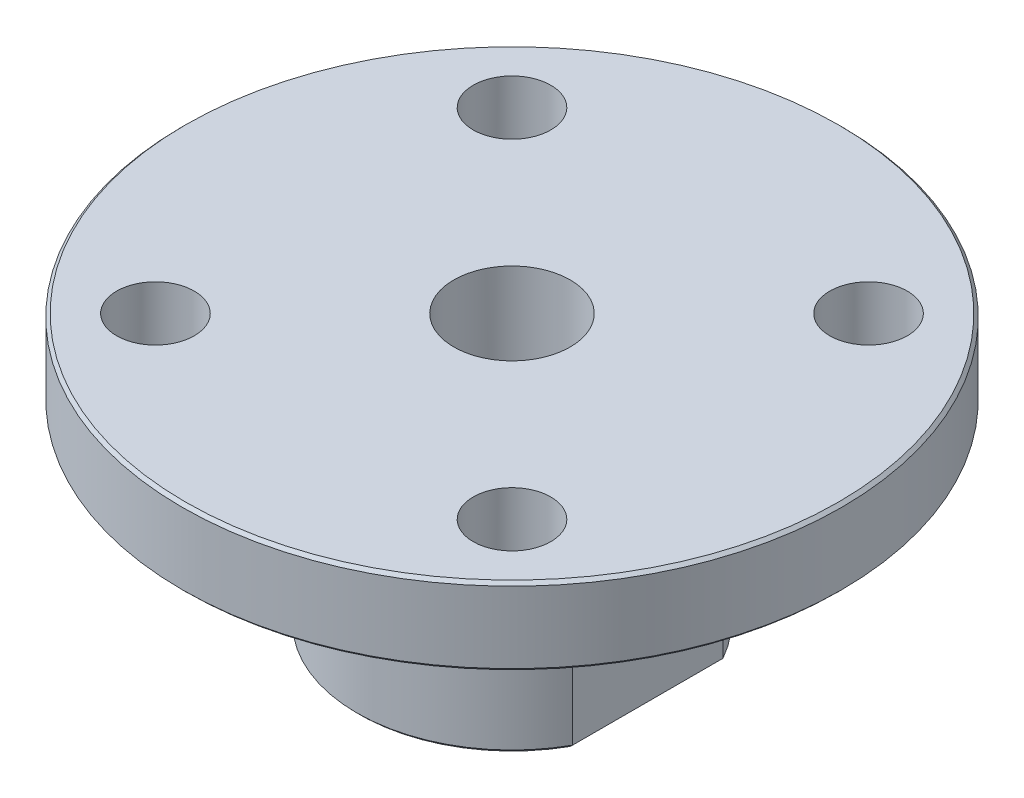
SolidWorks part; units mm, degrees
ref_plane "Front Plane" through (0, 0, 0) normal (0, 0, 1) x (1, 0, 0)
ref_plane "Top Plane" through (0, 0, 0) normal (0, 1, 0) x (1, 0, 0)
ref_plane "Right Plane" through (0, 0, 0) normal (1, 0, 0) x (0, 0, -1)
sketch "Sketch1" plane through (0, 0, 0) normal (0, 0, 1) x (1, 0, 0)
  line L0 (0, 0) -> (0, 50.6683) construction
  line L1 (6.35, 0) -> (6.35, 7.9375)
  line L2 (6.35, 7.9375) -> (13.4937, 7.9375)
  line L3 (13.4937, 7.9375) -> (13.4937, 11.1125)
  line L4 (13.4937, 11.1125) -> (2.3812, 11.1125)
  line L5 (6.35, 0) -> (2.3813, 0)
  line L6 (2.3813, 0) -> (2.3812, 11.1125)
  dimension "D1" = 7.9375
  dimension "D2" = 3.175
  dimension "D3" = 26.9875
  dimension "D4" = 4.7625
  dimension "D5" = 12.7
revolve "Revolve1" add sketch "Sketch1" angle 360 about L0
sketch "Sketch2" plane through (0, 0, 0) normal (0, -1, 0) x (1, 0, 0)
  line L0 (0, 0) -> (0, 11.4258) construction
  line L1 (7.1437, 3.0742) -> (5.5562, -3.0742) construction
  line L2 (-7.1437, -3.0742) -> (-5.5562, -3.0742)
  line L3 (-7.1437, -3.0742) -> (-7.1437, 3.0742)
  line L4 (-7.1437, 3.0742) -> (-5.5562, 3.0742)
  line L5 (-5.5562, -3.0742) -> (-5.5562, 3.0742)
  line L6 (-7.1437, -3.0742) -> (-5.5562, 3.0742) construction
  line L7 (-7.1437, 3.0742) -> (-5.5562, -3.0742) construction
  line L8 (7.1437, -3.0742) -> (5.5562, 3.0742) construction
  line L9 (5.5562, -3.0742) -> (5.5562, 3.0742)
  line L10 (7.1437, 3.0742) -> (5.5562, 3.0742)
  line L11 (7.1437, -3.0742) -> (7.1437, 3.0742)
  line L12 (7.1437, -3.0742) -> (5.5562, -3.0742)
  circle A0 centre (0, 0) radius 6.35 construction
  circle A1 centre (0, 0) radius 6.35 construction
  point P3 (-6.35, 0)
  point P16 (6.35, 0)
  dimension "D1" = 11.1125
extrude "Cut-Extrude1" cut sketch "Sketch2" against normal up to surface (7.9375 mm away) up to face at (0, 7.9375, -13.4937)
sketch "Sketch3" plane through (0, 0, 0) normal (1, 0, 0) x (0, 0, -1)
  circle A0 centre (0, 4.7625) radius 1.5875
  dimension "D1" = 3.175
  dimension "D2" = 4.7625
extrude "Cut-Extrude2" cut sketch "Sketch3" against normal through all
sketch "Sketch4" plane through (0, 11.1125, 0) normal (0, 1, 0) x (1, 0, 0)
  line L0 (0, 0) -> (-7.2965, 7.2965) construction
  line L1 (0, 0) -> (0, 10.3187) construction
  circle A0 centre (0, 0) radius 10.3187 construction
  circle A1 centre (-7.2965, 7.2965) radius 1.5875
  circle A2 centre (7.2965, 7.2965) radius 1.5875
  circle A3 centre (7.2965, -7.2965) radius 1.5875
  circle A4 centre (-7.2965, -7.2965) radius 1.5875
  dimension "D2" = 3.175
  dimension "D4" = 20.6375
  dimension "D1" = 45
  dimension "D3" = 4
extrude "Cut-Extrude3" cut sketch "Sketch4" against normal through all
chamfer "Chamfer1" distance 0.127 angle 45 6 edges at (5.5562, 0, 0) (0, 0, 6.35) (0, 0, -6.35) (-5.5562, 0, 0) (0, 7.9375, -13.4937) (0, 11.1125, -13.4937)
scale "Scale1" scale about centroid uniform scaling yes scale factor 0.8
